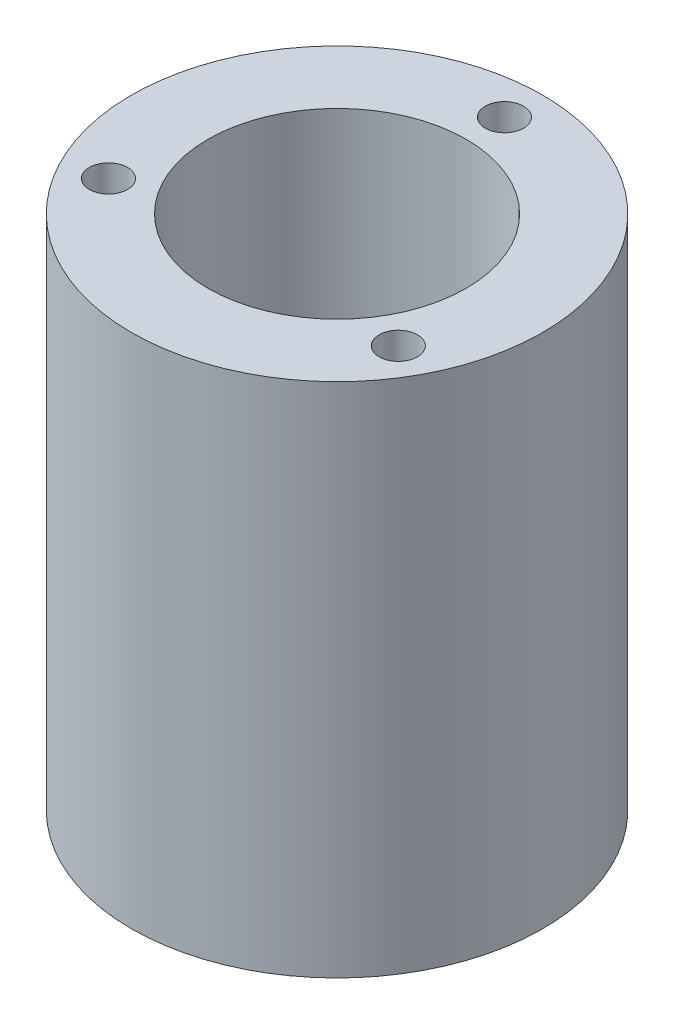
SolidWorks part; units mm, degrees
ref_plane "Front Plane" through (0, 0, 0) normal (0, 0, 1) x (1, 0, 0)
ref_plane "Top Plane" through (0, 0, 0) normal (0, 1, 0) x (1, 0, 0)
ref_plane "Right Plane" through (0, 0, 0) normal (1, 0, 0) x (0, 0, -1)
sketch "Sketch1" plane through (0, 0, 0) normal (0, 1, 0) x (1, 0, 0)
  circle A0 centre (0, 0) radius 21.5
extrude "Boss-Extrude1" add sketch "Sketch1" along normal blind 4
sketch "Sketch2" plane through (0, 4, 0) normal (0, 1, 0) x (1, 0, 0)
  circle A0 centre (0, 0) radius 21.5
  circle A1 centre (0, 0) radius 13.5
extrude "Boss-Extrude2" add sketch "Sketch2" along normal blind 50
sketch "Sketch3" plane through (0, 54, 0) normal (0, 1, 0) x (1, 0, 0)
  circle A0 centre (0, 17.5) radius 2
  dimension "D1" = 17.5
extrude "Cut-Extrude1" cut sketch "Sketch3" against normal blind 6
pattern_circular "CirPattern1" count 3 over 360 about axis through (0, 0, 0) along (0, 1, 0) of "Cut-Extrude1"
sketch "Sketch4" plane through (0, 0, 0) normal (0, -1, 0) x (1, 0, 0)
  line L1 (-1.5, -1.5) -> (1.5, -1.5)
  line L2 (-1.5, -1.5) -> (-1.5, 1.5)
  line L3 (-1.5, 1.5) -> (1.5, 1.5)
  line L4 (1.5, -1.5) -> (1.5, 1.5)
  point P7 (0.834, 2.2886)
  dimension "D1" = 1.5
  dimension "D2" = 1.5
  dimension "D3" = 1.5
extrude "Cut-Extrude2" cut sketch "Sketch4" against normal up to next
